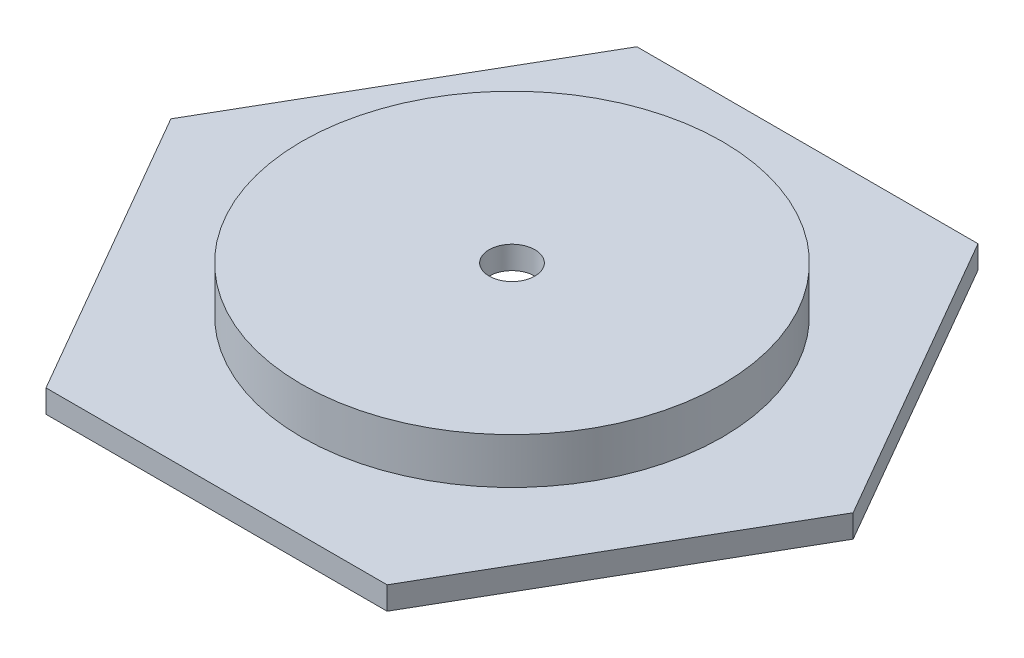
SolidWorks part; units mm, degrees
ref_plane "Front Plane" through (0, 0, 0) normal (0, 0, 1) x (1, 0, 0)
ref_plane "Top Plane" through (0, 0, 0) normal (0, 1, 0) x (1, 0, 0)
ref_plane "Right Plane" through (0, 0, 0) normal (1, 0, 0) x (0, 0, -1)
sketch "Sketch2" plane through (0, 0, 0) normal (0, 1, 0) x (1, 0, 0)
  line L1 (37.25, 0) -> (18.625, 32.2594)
  line L2 (18.625, 32.2594) -> (-18.625, 32.2594)
  line L3 (-18.625, 32.2594) -> (-37.25, 0)
  line L4 (-37.25, 0) -> (-18.625, -32.2594)
  line L5 (-18.625, -32.2594) -> (18.625, -32.2594)
  line L6 (18.625, -32.2594) -> (37.25, 0)
  circle A0 centre (0, 0) radius 32.2594 construction
  dimension "D1" = 37.25
extrude "Boss-Extrude1" add sketch "Sketch2" along normal blind 2.5
sketch "Sketch3" plane through (0, 0, 0) normal (0, -1, 0) x (1, 0, 0)
  circle A0 centre (0, 0) radius 2.5
  dimension "D1" = 5
extrude "Cut-Extrude1" cut sketch "Sketch3" against normal blind 2.5
sketch "Sketch4" plane through (0, 2.5, 0) normal (0, 1, 0) x (1, 0, 0)
  circle A0 centre (0, 0) radius 22.9668
extrude "Boss-Extrude2" add sketch "Sketch4" along normal blind 5
sketch "Sketch5" plane through (0, 0, 0) normal (0, -1, 0) x (1, 0, 0)
  circle A0 centre (0, 0) radius 20.8266
extrude "Cut-Extrude2" cut sketch "Sketch5" against normal blind 5
sketch "Sketch6" plane through (0, 5, 0) normal (0, -1, 0) x (1, 0, 0)
  circle A0 centre (0, 0) radius 2.5
  dimension "D1" = 5
extrude "Cut-Extrude3" cut sketch "Sketch6" against normal blind 5
